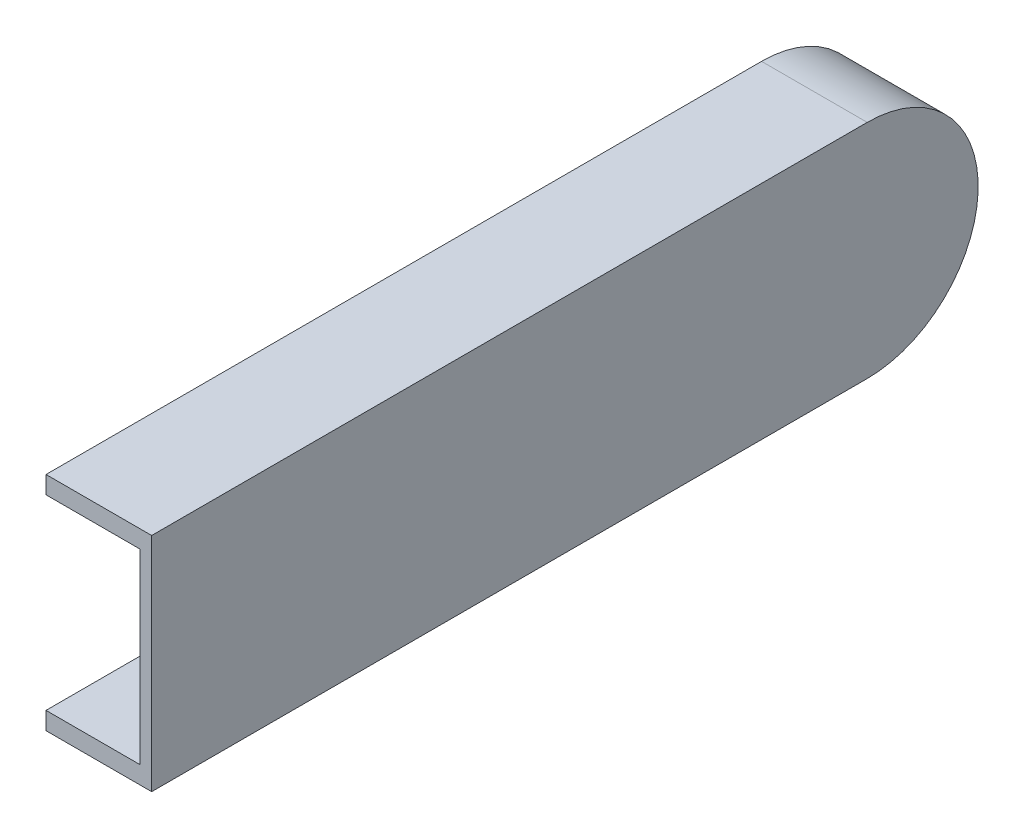
SolidWorks part; units mm, degrees
material "ABS"
ref_plane "Спереди" through (0, 0, 0) normal (0, 0, 1) x (1, 0, 0)
ref_plane "Сверху" through (0, 0, 0) normal (0, 1, 0) x (1, 0, 0)
ref_plane "Справа" through (0, 0, 0) normal (1, 0, 0) x (0, 0, -1)
sketch "Эскиз1" plane through (0, 0, 0) normal (1, 0, 0) x (0, 0, -1)
  line L0 (-30.4741, -9.45) -> (30.4741, -9.45)
  line L1 (30.4741, 9.45) -> (-30.4741, 9.45)
  line L2 (-30.4741, -7.95) -> (30.4741, -7.95)
  line L3 (30.4741, 7.95) -> (-30.4741, 7.95)
  arc A0 (-30.4741, 9.45) -> (-30.4741, -9.45) centre (-30.4741, 0) ccw
  arc A1 (30.4741, -9.45) -> (30.4741, 9.45) centre (30.4741, 0) ccw
  arc A2 (-30.4741, 7.95) -> (-30.4741, -7.95) centre (-30.4741, 0) ccw
  arc A3 (30.4741, -7.95) -> (30.4741, 7.95) centre (30.4741, 0) ccw
extrude "Бобышка-Вытянуть1" add sketch "Эскиз1" along normal blind 8
sketch "Эскиз2" plane through (8, 0, 0) normal (1, 0, 0) x (0, 0, -1)
  line L4 (-30.4741, -9.45) -> (30.4741, -9.45)
  line L5 (30.4741, 9.45) -> (-30.4741, 9.45)
  line L6 (-30.4741, -9.45) -> (30.4741, -9.45)
  line L7 (30.4741, 9.45) -> (-30.4741, 9.45)
  arc A4 (-30.4741, 9.45) -> (-30.4741, -9.45) centre (-30.4741, 0) ccw
  arc A5 (30.4741, -9.45) -> (30.4741, 9.45) centre (30.4741, 0) ccw
  arc A6 (-30.4741, 9.45) -> (-30.4741, -9.45) centre (-30.4741, 0) ccw
  arc A7 (30.4741, -9.45) -> (30.4741, 9.45) centre (30.4741, 0) ccw
  dimension "D1" = 0
extrude "Бобышка-Вытянуть2" add sketch "Эскиз2" along normal blind 1
sketch "Эскиз3" plane through (9, 0, 0) normal (1, 0, 0) x (0, 0, -1)
  line L0 (-30.4741, 9.45) -> (-30.4741, -9.45)
  line L1 (-30.4741, -9.45) -> (30.4741, -9.45) construction
  line L2 (-30.4741, -9.45) -> (-59.3482, -9.45)
  line L3 (-59.3482, -9.45) -> (-44.9111, 15.3757)
  line L4 (-44.9111, 15.3757) -> (-30.4741, 9.45)
  arc A0 (-30.4741, 9.45) -> (-30.4741, -9.45) centre (-30.4741, 0) ccw construction
extrude "Вырез-Вытянуть1" cut sketch "Эскиз3" against normal through all both and the other way through all
